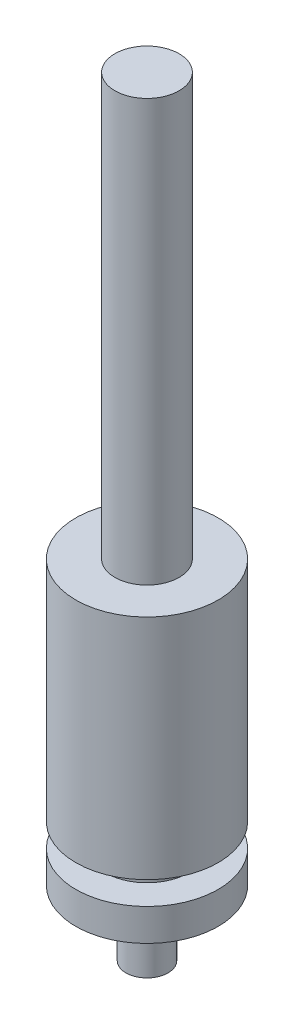
SolidWorks part; units mm, degrees
ref_plane "Front Plane" through (0, 0, 0) normal (0, 0, 1) x (1, 0, 0)
ref_plane "Top Plane" through (0, 0, 0) normal (0, 1, 0) x (1, 0, 0)
ref_plane "Right Plane" through (0, 0, 0) normal (1, 0, 0) x (0, 0, -1)
sketch "Sketch1" plane through (0, 0, 0) normal (0, 1, 0) x (1, 0, 0)
  circle A0 centre (0, 0) radius 16.891
  dimension "D1" = 33.782
extrude "Extrude1" add sketch "Sketch1" along normal blind 7.6
sketch "Sketch2" plane through (0, 7.6, 0) normal (0, 1, 0) x (1, 0, 0)
  circle A0 centre (0, 0) radius 9.9983
extrude "Extrude2" add sketch "Sketch2" along normal blind 5.5
sketch "Sketch3" plane through (0, 13.1, 0) normal (0, 1, 0) x (1, 0, 0)
  circle A0 centre (0, 0) radius 16.891
  dimension "D1" = 33.782
extrude "Extrude3" add sketch "Sketch3" along normal blind 53.975
sketch "Sketch4" plane through (0, 0, 0) normal (0, -1, 0) x (1, 0, 0)
  circle A0 centre (0, 0) radius 5.5
  dimension "D1" = 11
extrude "Boss-Extrude1" add sketch "Sketch4" along normal blind 15.5
sketch "Sketch5" plane through (0, -15.5, 0) normal (0, -1, 0) x (1, 0, 0)
  circle A0 centre (0, 0) radius 5
  circle A1 centre (0, 0) radius 5.5
  dimension "D1" = 10
extrude "Cut-Extrude1" cut sketch "Sketch5" against normal blind 9
sketch "Sketch6" plane through (0, 67.075, 0) normal (0, 1, 0) x (-1, 0, 0)
  circle A0 centre (0, 0) radius 7.62
  dimension "D1" = 15.24
extrude "Boss-Extrude2" add sketch "Sketch6" along normal blind 100
